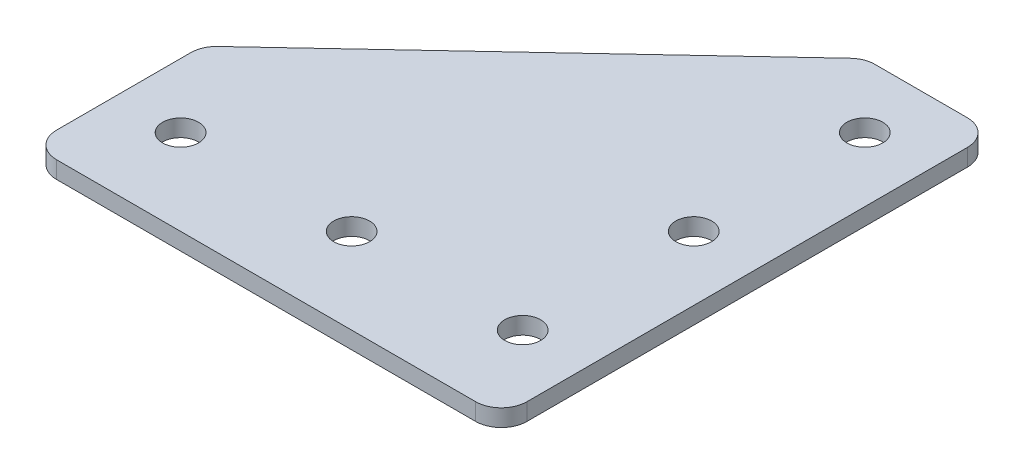
SolidWorks part; units mm, degrees
material "5052-H34"
ref_plane "正面" through (0, 0, 0) normal (0, 0, 1) x (1, 0, 0)
ref_plane "平面" through (0, 0, 0) normal (0, 1, 0) x (1, 0, 0)
ref_plane "右側面" through (0, 0, 0) normal (1, 0, 0) x (0, 0, -1)
sketch "ｽｹｯﾁ1" plane through (0, 0, 0) normal (0, 1, 0) x (1, 0, 0)
  line L0 (0, 0) -> (55, 0)
  line L3 (55, 57.5) -> (40, 57.5)
  line L4 (40, 57.5) -> (0, 20)
  line L5 (0, 20) -> (0, 0)
  line L6 (47.5, 0) -> (47.5, 57.5) construction
  line L7 (55, 10) -> (0, 10) construction
  line L8 (55, 57.5) -> (55, 0)
  circle A0 centre (7.5, 10) radius 2.1
  circle A2 centre (27.5, 10) radius 2.1
  circle A3 centre (47.5, 50) radius 2.1
  circle A6 centre (47.5, 30) radius 2.1
  circle A7 centre (47.5, 10) radius 2.1
  point P3 (50.5907, 0)
  point P19 (50.1301, 0)
  point P20 (43.0907, 10)
  point P21 (47.5, 0)
  dimension "D3" = 4.2
  dimension "D4" = 7.5
  dimension "D5" = 7.5
  dimension "D6" = 10
  dimension "D7" = 20
  dimension "D8" = 20
  dimension "D9" = 20
  dimension "D1" = 20
  dimension "D2" = 15
extrude "ﾎﾞｽ - 押し出し1" add sketch "ｽｹｯﾁ1" along normal blind 2
fillet "ﾌｨﾚｯﾄ1" radius 3 5 edges at (0, 1, -20) (0, 1, 0) (40, 1, -57.5) (55, 1, 0) (55, 1, -57.5)
